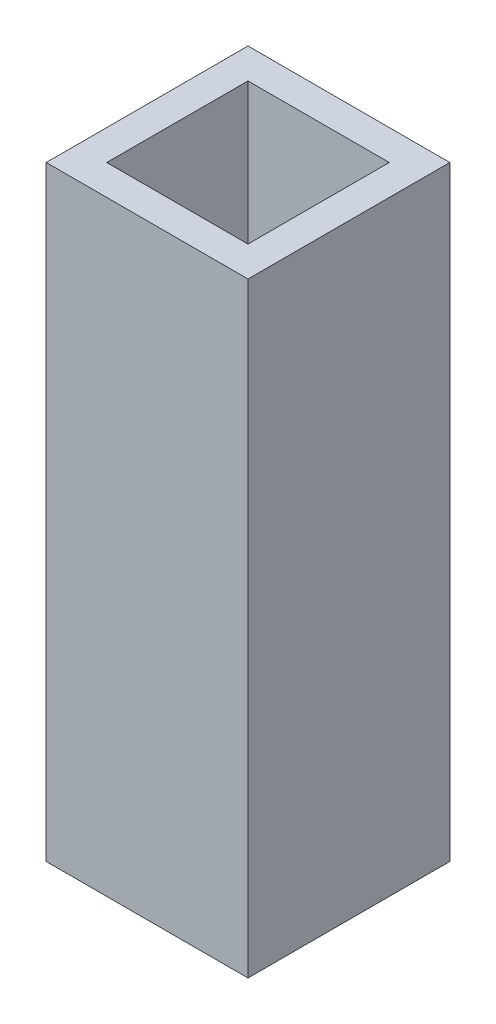
SolidWorks part; units mm, degrees
material "Plain Carbon Steel"
ref_plane "Front Plane" through (0, 0, 0) normal (0, 0, 1) x (1, 0, 0)
ref_plane "Top Plane" through (0, 0, 0) normal (0, 1, 0) x (1, 0, 0)
ref_plane "Right Plane" through (0, 0, 0) normal (1, 0, 0) x (0, 0, -1)
sketch "Sketch1" plane through (0, 0, 0) normal (0, 1, 0) x (1, 0, 0)
  line L1 (0, 0) -> (12.7, 0)
  line L2 (0, 0) -> (0, 12.7)
  line L3 (0, 12.7) -> (12.7, 12.7)
  line L4 (12.7, 0) -> (12.7, 12.7)
  line L5 (1.905, 10.795) -> (10.795, 10.795)
  line L6 (1.905, 10.795) -> (1.905, 1.905)
  line L7 (1.905, 1.905) -> (10.795, 1.905)
  line L8 (10.795, 10.795) -> (10.795, 1.905)
  dimension "D1" = 12.7
  dimension "D2" = 1.905
  dimension "D3" = 1.905
  dimension "D4" = 1.905
extrude "Boss-Extrude1" add sketch "Sketch1" along normal blind 38.1
